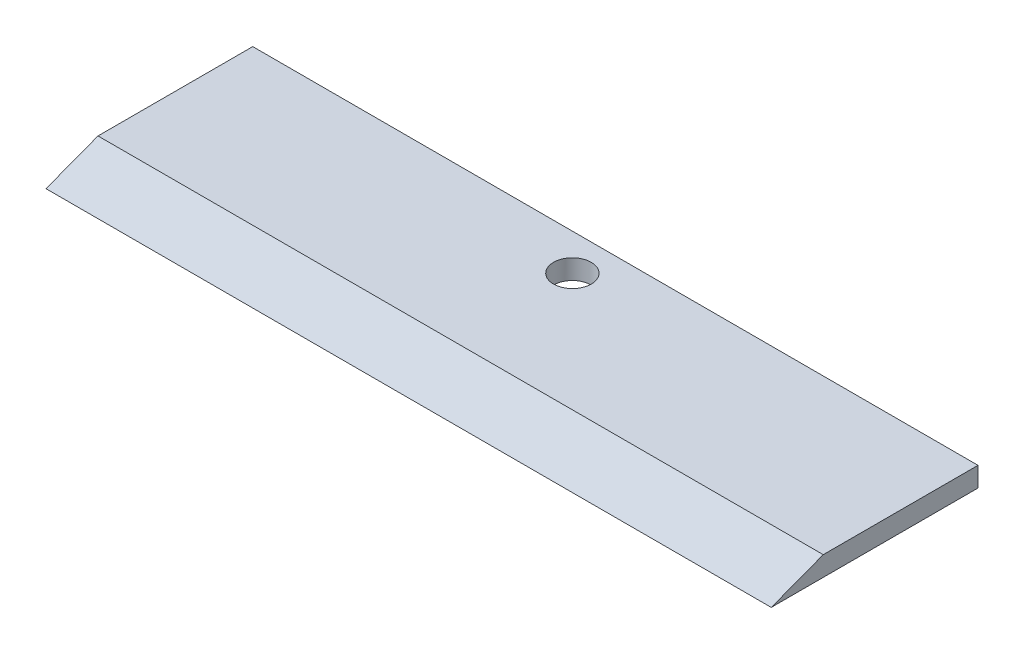
SolidWorks part; units mm, degrees
material "Plain Carbon Steel"
ref_plane "Front Plane" through (0, 0, 0) normal (0, 0, 1) x (1, 0, 0)
ref_plane "Top Plane" through (0, 0, 0) normal (0, 1, 0) x (1, 0, 0)
ref_plane "Right Plane" through (0, 0, 0) normal (1, 0, 0) x (0, 0, -1)
sketch "Sketch1" plane through (0, 0, 0) normal (0, 1, 0) x (1, 0, 0)
  line L1 (0, 0) -> (22.1, 0)
  line L2 (0, 0) -> (0, 6.3)
  line L3 (0, 6.3) -> (22.1, 6.3)
  line L4 (22.1, 0) -> (22.1, 6.3)
  dimension "D1" = 6.3
  dimension "D2" = 22.1
extrude "Boss-Extrude1" add sketch "Sketch1" along normal blind 0.6
sketch "Sketch3" plane through (22.1, 0, 0) normal (1, 0, 0) x (0, 0, -1)
  line L0 (0, 0) -> (1.5845, 0.6)
  line L1 (0, 0.6) -> (6.3, 0.6) construction
  line L2 (1.5845, 0.6) -> (1.5845, 0)
  line L3 (0, 0) -> (6.3, 0) construction
  line L4 (1.5845, 0) -> (0, 0)
  line L5 (1.5845, 0.6) -> (0, 0.6)
  line L6 (0, 0.6) -> (0, 0)
  line M3 (6.3, 0.6) -> (0, 0.6)
  line M4 (0, 0.6) -> (0, 0)
extrude "Cut-Extrude1" cut sketch "Sketch3" against normal blind 24.73 contours L0 M4 M3
sketch "Sketch4" plane through (0, 0.6, 0) normal (0, 1, 0) x (1, 0, 0)
  circle A1 centre (10.85, 5.1899) radius 0.575
  circle A2 centre (10.85, 5.1899) radius 0.575
  dimension "D1" = 0
extrude "Cut-Extrude2" cut sketch "Sketch4" against normal blind 2.54
